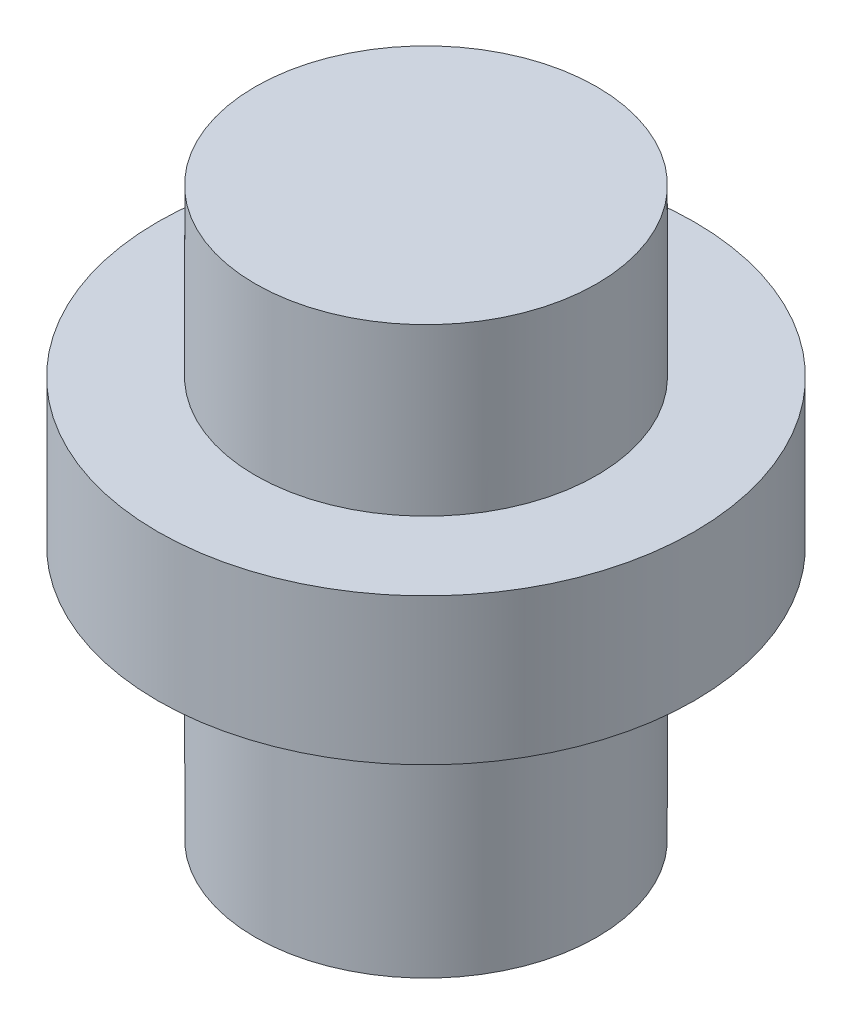
SolidWorks part; units mm, degrees
ref_plane "前视基准面" through (0, 0, 0) normal (0, 0, 1) x (1, 0, 0)
ref_plane "上视基准面" through (0, 0, 0) normal (0, 1, 0) x (1, 0, 0)
ref_plane "右视基准面" through (0, 0, 0) normal (1, 0, 0) x (0, 0, -1)
other "Configuration Table"
sketch "草图1" plane through (0, -8.55, 0) normal (0, -1, 0) x (1, 0, 0)
  circle A1 centre (24.0914, -9.5462) radius 1.75
  circle A2 centre (24.0914, -9.5462) radius 1.75
  dimension "D1" = 0
extrude "凸台-拉伸1" add sketch "草图1" along normal blind 5.8
sketch "草图2" plane through (0, -10.25, 0) normal (0, 1, 0) x (1, 0, 0)
  circle A0 centre (24.0914, 9.5462) radius 1.75 construction
  circle A1 centre (24.0914, 9.5462) radius 1.75
extrude "拉伸-薄壁1" add sketch "草图2" against normal blind 1.5 thin
